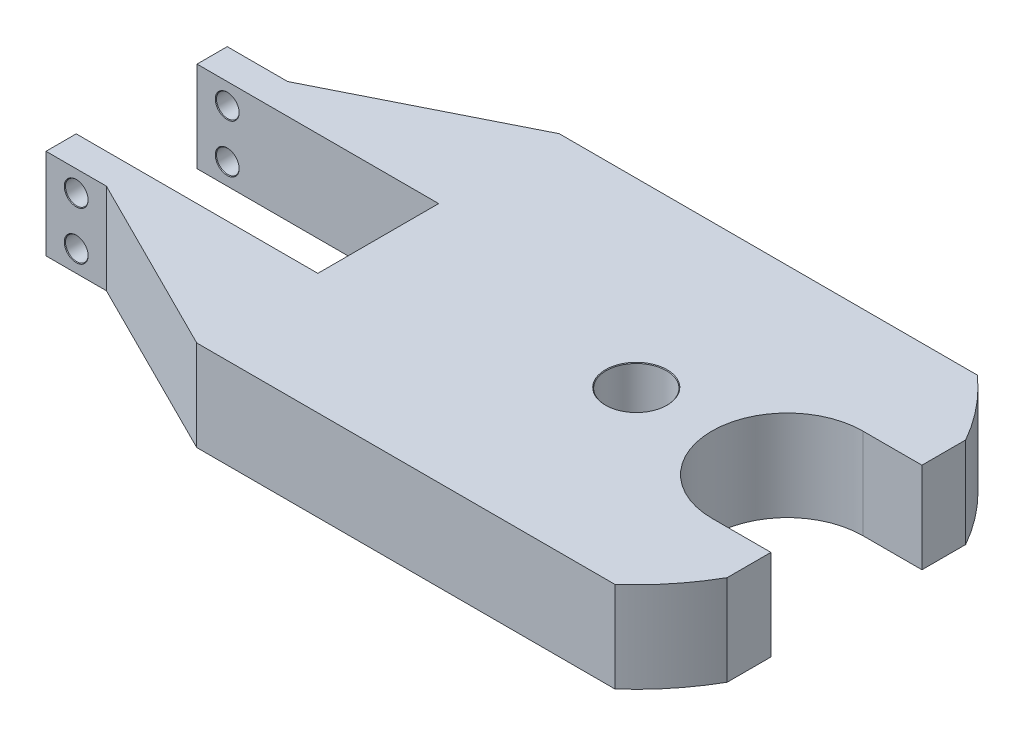
SolidWorks part; units mm, degrees
ref_plane "Front Plane" through (0, 0, 0) normal (0, 0, 1) x (1, 0, 0)
ref_plane "Top Plane" through (0, 0, 0) normal (0, 1, 0) x (1, 0, 0)
ref_plane "Right Plane" through (0, 0, 0) normal (1, 0, 0) x (0, 0, -1)
sketch "Sketch2" plane through (0, 0, 0) normal (0, 1, 0) x (1, 0, 0)
  line L0 (-112.0719, 0) -> (171.9866, 0) construction
  line L1 (0, -25.4) -> (0, 25.4)
  line L2 (0, 25.4) -> (-101.6, 25.4)
  line L3 (-101.6, 25.4) -> (-101.6, 38.1)
  line L4 (-101.6, 38.1) -> (-76.2, 38.1)
  line L5 (-76.2, 38.1) -> (-0.1165, 76.2)
  line L6 (-0.1165, 76.2) -> (175.6887, 76.2)
  line L7 (196.85, 50.1445) -> (196.85, 31.75)
  line L8 (171.9866, 31.75) -> (196.85, 31.75)
  line L9 (171.9866, 0) -> (197.3866, 0) construction
  line L10 (171.9866, -31.75) -> (196.85, -31.75)
  line L11 (196.85, -50.1445) -> (196.85, -31.75)
  line L12 (-0.1165, -76.2) -> (175.6887, -76.2)
  line L13 (-76.2, -38.1) -> (-0.1165, -76.2)
  line L14 (-101.6, -38.1) -> (-76.2, -38.1)
  line L15 (-101.6, -25.4) -> (-101.6, -38.1)
  line L16 (0, -25.4) -> (-101.6, -25.4)
  arc A0 (171.9866, 31.75) -> (171.9866, -31.75) centre (171.9866, 0) ccw
  arc A1 (175.6887, 76.2) -> (196.85, 50.1445) centre (108.4866, 0) cw
  arc A2 (175.6887, -76.2) -> (196.85, -50.1445) centre (108.4866, 0) ccw
  circle A3 centre (108.4866, 0) radius 12.7
  point P5 (-101.6, 31.75)
  point P27 (0, 0)
  dimension "D9" = 31.75
  dimension "D11" = 101.6
  dimension "D1" = 25.4
  dimension "D2" = 101.6
  dimension "D3" = 85.09
  dimension "D4" = 298.45
  dimension "D5" = 76.2
  dimension "D6" = 25.4
  dimension "D7" = 38.1
  dimension "D8" = 25.4
  dimension "D10" = 63.5
extrude "Boss-Extrude1" add sketch "Sketch2" along normal blind 38.1
sketch "Sketch4" plane through (0, 0, 0) normal (-1, 0, 0) x (0, 0, 1)
  line L0 (-25.4, 0) -> (25.4, 0) construction
  circle A0 centre (0, 19.05) radius 9.525
  dimension "D1" = 19.05
  dimension "D2" = 19.05
extrude "Cut-Extrude1" cut sketch "Sketch4" against normal blind 19.05
sketch "Sketch5" plane through (0, 0, 38.1) normal (0, 0, 1) x (1, 0, 0)
  line L0 (-101.6, 19.05) -> (-76.2, 19.05) construction
  line L1 (-101.6, 38.1) -> (-101.6, 0) construction
  line L2 (-76.2, 38.1) -> (-76.2, 0) construction
  line L3 (-101.6, 38.1) -> (-76.2, 38.1) construction
  circle A0 centre (-88.9, 29.21) radius 4.7625
  circle A1 centre (-88.9, 8.89) radius 4.7625
  dimension "D3" = 9.525
  dimension "D1" = 8.89
  dimension "D2" = 12.7
extrude "Cut-Extrude2" cut sketch "Sketch5" against normal through all
chamfer "Chamfer1" distance 0.254 angle 45 10 edges at (-84.1375, 29.21, 38.1) (108.4866, 0, 12.7) (108.4866, 38.1, 12.7) (-93.6625, 8.89, -25.4) (-84.1375, 8.89, -38.1) (-93.6625, 29.21, -25.4) (-84.1375, 29.21, -38.1) (-84.1375, 8.89, 25.4) (-93.6625, 8.89, 38.1) (0, 19.05, 9.525)
